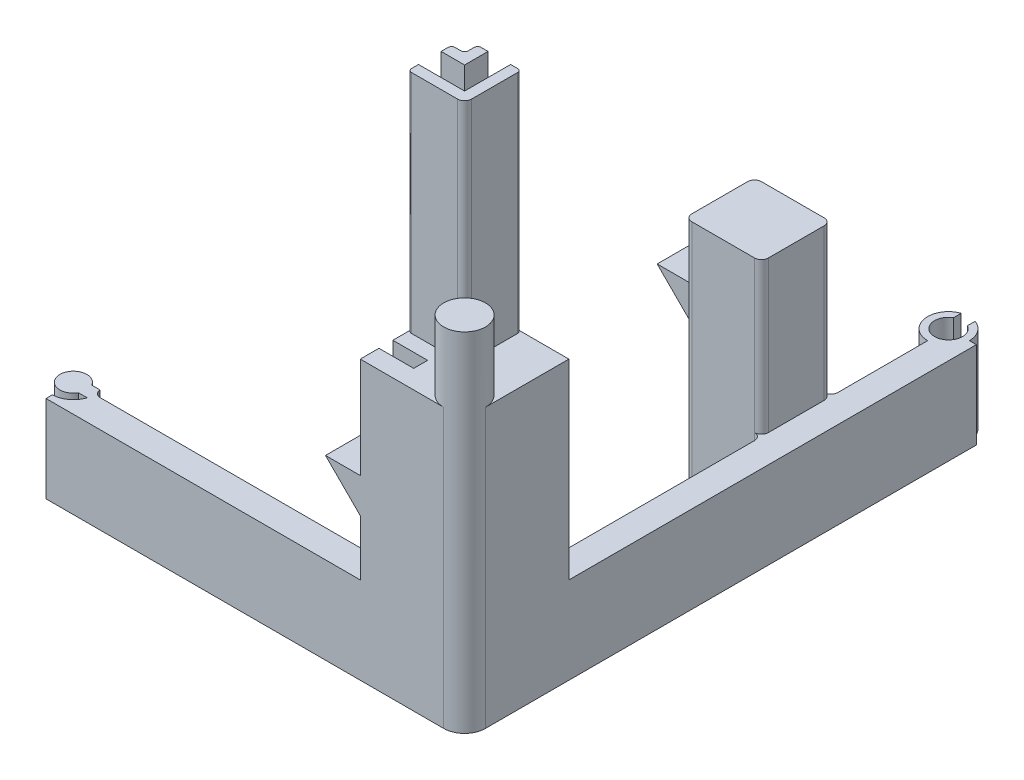
SolidWorks part; units mm, degrees
ref_plane "Front Plane" through (0, 0, 0) normal (0, 0, 1) x (1, 0, 0)
ref_plane "Top Plane" through (0, 0, 0) normal (0, 1, 0) x (1, 0, 0)
ref_plane "Right Plane" through (0, 0, 0) normal (1, 0, 0) x (0, 0, -1)
sketch "Sketch1" plane through (0, 0, 0) normal (0, 1, 0) x (1, 0, 0)
  line L1 (-15, -15) -> (15, -15)
  line L2 (-15, -15) -> (-15, 15)
  line L3 (-15, 15) -> (15, 15)
  line L4 (15, -15) -> (15, 15)
  line L5 (-15, -15) -> (15, 15) construction
  line L6 (-15, 15) -> (15, -15) construction
  point P0 (0, 0)
  dimension "D1" = 30
extrude "Boss-Extrude1" add sketch "Sketch1" along normal blind 80
sketch "Sketch2" plane through (0, 80, 0) normal (0, 1, 0) x (1, 0, 0)
  line L0 (-15, -15) -> (15, -15) construction
  line L1 (15, -15) -> (15, 15) construction
  circle A0 centre (9, -9) radius 6
  dimension "D1" = 12
extrude "Boss-Extrude2" add sketch "Sketch2" along normal blind 20
sketch "Sketch3" plane through (0, 80, 0) normal (0, 1, 0) x (1, 0, 0)
  line L2 (9, -15) -> (15, -15)
  line L4 (15, -15) -> (15, -9)
  circle A1 centre (9, -9) radius 6
  arc A4 (9, -15) -> (15, -9) centre (9, -9) ccw
  dimension "D1" = 0
extrude "Cut-Extrude1" cut sketch "Sketch3" against normal through all
sketch "Sketch4" plane through (0, 80, 0) normal (0, 1, 0) x (1, 0, 0)
  line L1 (-8.25, 11.25) -> (-1.75, 11.25) construction
  line L2 (-8.25, 11.25) -> (-8.25, 8.25)
  line L6 (-1.75, 1.75) -> (-11.25, 1.75)
  line L8 (-8.25, 8.25) -> (-11.25, 8.25)
  line L9 (-11.25, 1.75) -> (-11.25, 8.25) construction
  line L10 (-1.75, 11.25) -> (-1.75, 1.75)
  line L11 (-11.25, -1.25) -> (1.25, -1.25)
  line L12 (1.25, -1.25) -> (1.25, 11.25)
  line L13 (1.25, 11.25) -> (-1.75, 11.25) construction
  line L14 (-11.25, 1.75) -> (-11.25, -1.25) construction
  line L15 (-11.25, 8.25) -> (-11.25, 11.25) construction
  line L16 (-11.25, 11.25) -> (-8.25, 11.25) construction
  line L17 (-8.25, 11.25) -> (-8.25, 15)
  line L18 (15, 15) -> (-15, 15) construction
  line L19 (-8.25, 15) -> (-11.25, 15)
  line L20 (-11.25, 15) -> (-11.25, 11.25)
  line L21 (-11.25, 11.25) -> (-15, 11.25)
  line L22 (-15, 15) -> (-15, -15) construction
  line L23 (-15, 11.25) -> (-15, 8.25)
  line L24 (-15, 8.25) -> (-11.25, 8.25)
  line L25 (1.25, 15) -> (-1.75, 15)
  line L26 (-1.75, 15) -> (-1.75, 11.25)
  line L27 (1.25, 15) -> (1.25, 11.25)
  line L28 (-11.25, 1.75) -> (-15, 1.75)
  line L29 (-15, 1.75) -> (-15, -1.25)
  line L30 (-15, -1.25) -> (-11.25, -1.25)
  dimension "D1" = 6.5
  dimension "D2" = 3
  dimension "D3" = 3.75
extrude "Boss-Extrude3" add sketch "Sketch4" along normal blind 65
sketch "Sketch6" plane through (0, 0, 0) normal (0, -1, 0) x (1, 0, 0)
  line L1 (15, -15) -> (7, -15)
  line L2 (15, -15) -> (15, -132.175)
  line L3 (15, -132.175) -> (13, -132.175)
  line L4 (7, -15) -> (7, -126.175)
  arc A1 (7, -126.175) -> (13, -132.175) centre (7, -132.175) ccw
  dimension "D3" = 12
  dimension "D1" = 117.175
  dimension "D2" = 8
extrude "Boss-Extrude5" add sketch "Sketch6" against normal blind 2
sketch "Sketch7" plane through (0, 2, 0) normal (0, 1, 0) x (1, 0, 0)
  line L0 (7, 136.175) -> (7, 138.175) construction
  line L1 (9, 137.8319) -> (9, 135.6391)
  line L2 (5, 137.8319) -> (5, 135.6391)
  line L3 (7, 128.175) -> (7, 126.175) construction
  line L4 (15, 132.175) -> (13, 132.175)
  line L5 (15, 132.175) -> (15, 15)
  line L6 (15, 15) -> (7, 15)
  line L7 (7, 15) -> (7, 126.175) construction
  line L8 (15, 15) -> (1.25, 15) construction
  line L9 (7, 15) -> (7, 126.175)
  arc A0 (5, 137.8319) -> (7, 126.175) centre (7, 132.175) ccw
  arc A1 (13, 132.175) -> (7, 126.175) centre (7, 132.175) ccw construction
  arc A2 (5, 135.6391) -> (9, 135.6391) centre (7, 132.175) ccw
  arc A3 (13, 132.175) -> (9, 137.8319) centre (7, 132.175) ccw
  dimension "D1" = 2
  dimension "D2" = 2
extrude "Boss-Extrude6" add sketch "Sketch7" along normal offset from surface (23 mm away) 25 up to face at (3.75, 0, -48.4406)
sketch "Sketch9" plane through (0, 0, 0) normal (0, -1, 0) x (1, 0, 0)
  line L0 (15, -15) -> (7, -15) construction
  line L1 (-15, 15) -> (-105.5, 15) construction
  line L2 (-15, 15) -> (-15, 7)
  line L3 (-15, 7) -> (-99.5, 7) construction
  line L4 (-105.5, 15) -> (-105.5, 13.1746) construction
  line L5 (-109.375, 7) -> (-109.5, 7) construction
  line L6 (-101.5, 7) -> (-99.5, 7) construction
  line L7 (-99.5, 9) -> (-102.181, 9) construction
  line L8 (7, -136.175) -> (7, -138.175) construction
  line L9 (9, -137.8319) -> (5, -137.8319) construction
  line L10 (-99.5, 5) -> (-102.181, 5) construction
  line L11 (-99.5, 9) -> (-99.5, 5) construction
  line L12 (-102.1228, 8.9) -> (-99.625, 8.9)
  line L13 (-102.1228, 5.1) -> (-99.5, 5.1) construction
  line L14 (-99.5, 5.1) -> (-99.5, 7) construction
  line L15 (-99.5, 8.9) -> (-99.625, 8.9) construction
  line L16 (-105.375, 15) -> (-105.375, 13.1733)
  line L17 (-105.375, 14.0867) -> (-105.5, 14.0873) construction
  line L18 (-105.375, 15) -> (-15, 15)
  line L19 (-99.5, 5.1) -> (-99.5, 7) construction
  line L20 (-15, 7) -> (-99.5, 7)
  line L21 (-99.8088, 5.1) -> (-102.1228, 5.1)
  circle A0 centre (-105.5, 7) radius 4 construction
  arc A1 (9, -135.6391) -> (5, -135.6391) centre (7, -132.175) ccw construction
  arc A2 (-102.1228, 8.9) -> (-102.1228, 5.1) centre (-105.5, 7) ccw
  arc A4 (-99.625, 8.9) -> (-105.5, 13.1746) centre (-105.5, 7) ccw construction
  arc A6 (-99.625, 8.9) -> (-105.375, 13.1733) centre (-105.5, 7) ccw
  arc A7 (-99.8088, 5.1) -> (-99.5, 7) centre (-105.5, 7) ccw
  arc A8 (7, -126.175) -> (5, -137.8319) centre (7, -132.175) ccw construction
  dimension "D1" = 90.5
  dimension "D2" = 0.125
  dimension "D3" = 1.9
extrude "Boss-Extrude7" add sketch "Sketch9" against normal blind 25
fillet "Fillet1" radius 2 1 edges at (-99.5, 12.5, 7)
sketch "Sketch11" plane through (0, 0, 0) normal (0, -1, 0) x (1, 0, 0)
  line L0 (-99.625, 8.9) -> (-99.75, 8.9) construction
  line L2 (-99.625, 8.9) -> (-102.1228, 8.9) construction
  line L3 (-109.375, 7) -> (-109.5, 7) construction
  circle A0 centre (-105.5, 7) radius 6.0558
  arc A5 (-102.1228, 8.9) -> (-102.1228, 5.1) centre (-105.5, 7) ccw construction
extrude "Cut-Extrude2" cut sketch "Sketch11" against normal offset from surface (2.125 mm away) 0.125 up to face at (7, 2, -134.9552) offset beyond the face yes
sketch "Sketch12" plane through (0, 0, -15) normal (0, 0, -1) x (-1, 0, 0)
  line L0 (15, 80) -> (15, 0) construction
  line L1 (15, 77) -> (1.75, 77)
  line L2 (15, 77) -> (15, 68.5)
  line L3 (15, 68.5) -> (1.75, 68.5)
  line L4 (1.75, 77) -> (1.75, 68.5)
  line L9 (1.75, 80) -> (15, 80) construction
  line L11 (1.75, 145) -> (1.75, 80) construction
  dimension "D1" = 3
  dimension "D2" = 8.5
extrude "Cut-Extrude3" cut sketch "Sketch12" against normal up to surface (13.25 mm away) up to face at (-8.375, 112.5, -1.75)
sketch "Sketch13" plane through (15, 0, 0) normal (1, 0, 0) x (0, 0, -1)
  line L0 (138.175, 0) -> (-15, 0) construction
fillet "Fillet2" radius 2 1 edges at (1.25, 112.5, 1.25)
sketch "Sketch14" plane through (0, 80, 0) normal (0, 1, 0) x (1, 0, 0)
  line L4 (-11.25, 11.25) -> (-11.25, 15)
  line L5 (-11.25, 15) -> (-15, 15)
  line L6 (-15, 15) -> (-15, 11.25)
  line L7 (-15, 11.25) -> (-11.25, 11.25)
  line L8 (-11.25, 11.25) -> (-11.25, 15)
  line L9 (-11.25, 15) -> (-15, 15)
  line L10 (-15, 15) -> (-15, 11.25)
  line L11 (-15, 11.25) -> (-11.25, 11.25)
  dimension "D1" = 0
extrude "Cut-Extrude4" cut sketch "Sketch14" against normal up to next
fillet "Fillet3" radius 1 5 edges at (-15, 112.5, 1.25) (1.25, 112.5, -15) (-11.25, 111, -15) (-11.25, 111, -11.25) (-15, 111, -11.25)
sketch "Sketch15" plane through (0, 80, 0) normal (0, 1, 0) x (1, 0, 0)
  line L0 (-15, -0.25) -> (-15, -15) construction
  line L1 (-15, -9.625) -> (-5, -9.625)
  line L2 (-15, -9.625) -> (-15, -5.625)
  line L3 (-15, -5.625) -> (-5, -5.625)
  line L4 (-5, -9.625) -> (-5, -5.625)
  point P6 (-15, -7.625)
  point P7 (-15, -7.625)
  dimension "D1" = 4
  dimension "D2" = 10
extrude "Cut-Extrude5" cut sketch "Sketch15" against normal blind 25
sketch "Sketch17" plane through (0, 0, 0) normal (0, -1, 0) x (1, 0, 0)
  line L0 (7, -15) -> (7, -126.175) construction
  line L1 (7, -98.3813) -> (-15, -98.3813)
  line L2 (7, -98.3813) -> (7, -78.3813)
  line L3 (7, -78.3813) -> (-15, -78.3813)
  line L4 (-15, -98.3813) -> (-15, -78.3813)
  line L5 (-15, -15) -> (-15, 7) construction
  line L6 (7, -126.175) -> (7, -70.5875) construction
  point P12 (7, -98.3813)
  dimension "D1" = 20
extrude "Boss-Extrude8" add sketch "Sketch17" against normal up to surface (68.5 mm away) up to face at (-8.375, 68.5, -8.375)
sketch "Sketch18" plane through (0, 0, 0) normal (0, -1, 0) x (1, 0, 0)
  line L0 (-12.5, -78.3813) -> (-12.5, -80.8813) construction
  line L1 (-12.5, -80.8813) -> (4.5, -80.8813)
  line L2 (-12.5, -80.8813) -> (-12.5, -95.8813)
  line L3 (-12.5, -95.8813) -> (4.5, -95.8813)
  line L4 (4.5, -80.8813) -> (4.5, -95.8813)
  line L5 (7, -78.3813) -> (-15, -78.3813) construction
  line L6 (-12.5, -80.8813) -> (-15, -80.8813) construction
  line L7 (-15, -78.3813) -> (-15, -98.3813) construction
  line L8 (7, -78.3813) -> (7, -98.3813) construction
  line L9 (7, -88.3813) -> (4.5, -88.3813) construction
  point P17 (4.5, -88.3813)
  dimension "D1" = 2.5
extrude "Cut-Extrude6" cut sketch "Sketch18" against normal offset from surface (66 mm away) 2.5 up to face at (-4, 68.5, -88.3813)
fillet "Fillet4" radius 2 4 edges at (7, 12.5, -78.3813) (7, 12.5, -98.3813) (-15, 34.25, -98.3813) (-15, 34.25, -78.3813)
fillet "Fillet5" radius 2 2 edges at (7, 46.75, -78.3813) (7, 46.75, -98.3813)
chamfer "Chamfer1" distance 7 angle 45 4 edges at (-4, 66, -80.8813) (4.5, 66, -88.3813) (-4, 66, -95.8813) (-12.5, 66, -88.3813)
sketch "Sketch19" plane through (0, 0, 15) normal (0, 0, 1) x (1, 0, 0)
  line L0 (-15, 41) -> (-15, 51)
  line L1 (-15, 80) -> (-15, 25) construction
  line L2 (-15, 51) -> (-25, 51)
  line L3 (-25, 51) -> (-15, 41)
  line L4 (-15, 51) -> (-15, 55) construction
  line L6 (-5, 55) -> (-15, 55) construction
  line L7 (-5, 55) -> (-15, 55) construction
  point P8 (-15, 69.1425)
  dimension "D1" = 10
  dimension "D2" = 4
extrude "Boss-Extrude9" add sketch "Sketch19" against normal up to surface (30 mm away) up to face at (-1.8437, 77.5625, -15)
ref_plane "Plane1" through (0, 0, -88.3813) normal (0, 0, 1) x (1, 0, 0)
sketch "Sketch20" plane through (0, 0, -88.3813) normal (0, 0, 1) x (1, 0, 0)
  line L3 (-15, 41) -> (-15, 51)
  line L4 (-15, 51) -> (-25, 51)
  line L5 (-25, 51) -> (-15, 41)
  line L6 (-15, 41) -> (-15, 51)
  line L7 (-15, 51) -> (-25, 51)
  line L8 (-25, 51) -> (-15, 41)
  dimension "D1" = 0
extrude "Boss-Extrude10" add sketch "Sketch20" along normal up to vertex and the other way up to vertex
